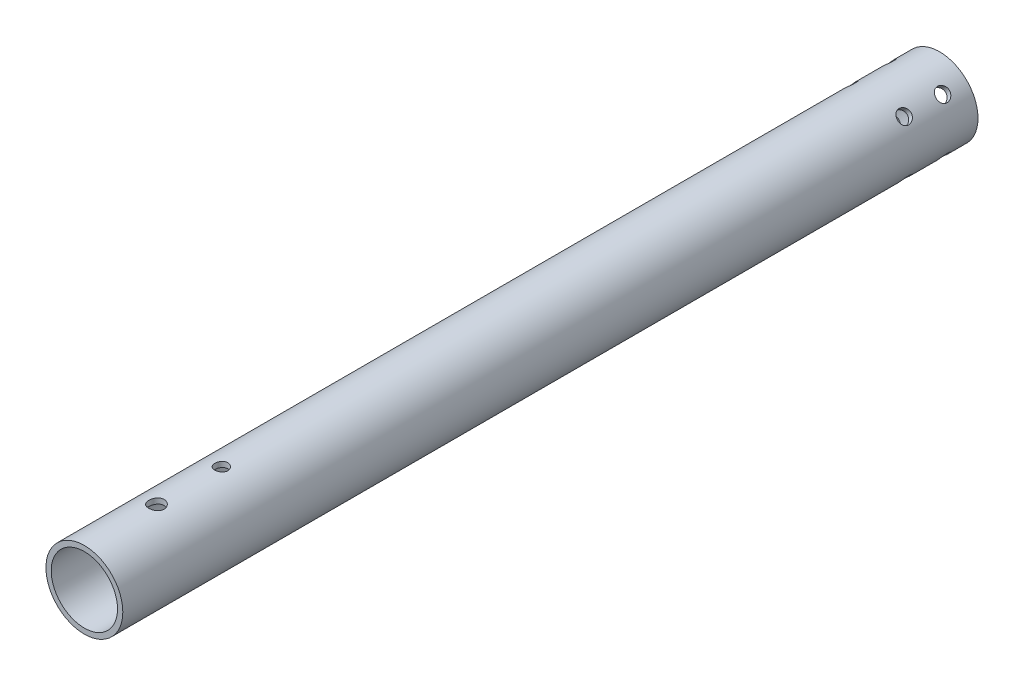
SolidWorks part; units mm, degrees
ref_plane "Front Plane" through (0, 0, 0) normal (0, 0, 1) x (1, 0, 0)
ref_plane "Top Plane" through (0, 0, 0) normal (0, 1, 0) x (1, 0, 0)
ref_plane "Right Plane" through (0, 0, 0) normal (1, 0, 0) x (0, 0, -1)
sketch "Sketch1" plane through (0, 0, 0) normal (0, 0, 1) x (1, 0, 0)
  circle A0 centre (0, 0) radius 8
  circle A1 centre (0, 0) radius 6.9
  dimension "D1" = 16
  dimension "D2" = 13.8
extrude "Boss-Extrude1" add sketch "Sketch1" along normal blind 163
sketch "Sketch2" plane through (0, 0, 0) normal (0, 1, 0) x (1, 0, 0)
  line L0 (-8, -163) -> (8, -163) construction
  line L1 (8, 0) -> (-8, 0) construction
  circle A1 centre (0, -163) radius 1.6
  arc A11 (0, -148.475) -> (0, -150.525) centre (0, -149.5) ccw construction
  arc A12 (0, -148.475) -> (0, -150.525) centre (0, -149.5) ccw construction
  circle A14 centre (0, -149.5) radius 1.35
  point P10 (-0.0846, -149.5)
  dimension "D1" = 163
  dimension "D2" = 3.2
  dimension "D3" = 2.7
sketch "Sketch3" plane through (0, 0, 163) normal (0, 0, 1) x (1, 0, 0)
  circle A0 centre (0, 0) radius 6.9 construction
  circle A1 centre (0, 0) radius 8 construction
  circle A2 centre (0, 0) radius 6.9
  circle A3 centre (0, 0) radius 8
extrude "Boss-Extrude3" add sketch "Sketch3" along normal blind 15
extrude "Cut-Extrude1" cut sketch "Sketch2" against normal through all and the other way through all
ref_axis "Axis1" through (0, 0, -8.9) along (0, 0, 1)
ref_plane "Plane1" through (0, 0, 0) normal (0.7071, 0.7071, 0) x (0, 0, 1)
sketch "Sketch4" plane through (0, 0, 0) normal (0.7071, 0.7071, 0) x (0, 0, 1)
  circle A0 centre (13, 0) radius 1.4 construction
  circle A1 centre (5, 0) radius 1.4 construction
  circle A2 centre (13, 0) radius 1.4
  circle A3 centre (5, 0) radius 1.4
extrude "Cut-Extrude2" cut sketch "Sketch4" against normal through all and the other way through all
pattern_circular "CirPattern1" count 2 over 90 about axis through (0, 0, -8.9) along (0, 0, 1) of "Cut-Extrude2"
